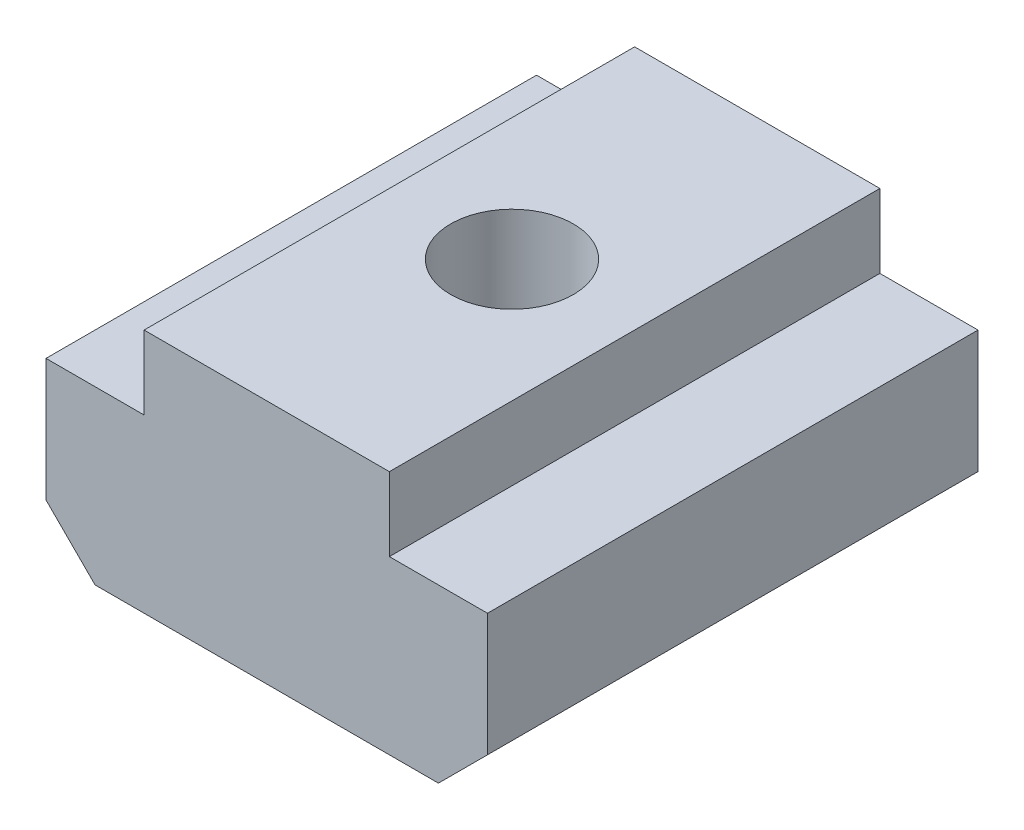
SolidWorks part; units mm, degrees
ref_plane "Front Plane" through (0, 0, 0) normal (0, 0, 1) x (1, 0, 0)
ref_plane "Top Plane" through (0, 0, 0) normal (0, 1, 0) x (1, 0, 0)
ref_plane "Right Plane" through (0, 0, 0) normal (1, 0, 0) x (0, 0, -1)
sketch "Sketch1" plane through (0, 0, 0) normal (0, 0, 1) x (1, 0, 0)
  line L0 (0, 0) -> (0, 46.9655) construction
  line L1 (-3.5, 0) -> (3.5, 0)
  line L2 (3.5, 0) -> (4.5, 1)
  line L3 (4.5, 1) -> (4.5, 3.5)
  line L4 (4.5, 3.5) -> (2.5, 3.5)
  line L5 (2.5, 3.5) -> (2.5, 5)
  line L6 (2.5, 5) -> (-2.5, 5)
  line L7 (-2.5, 5) -> (-2.5, 3.5)
  line L8 (-2.5, 3.5) -> (-4.5, 3.5)
  line L9 (-4.5, 3.5) -> (-4.5, 1)
  line L10 (-4.5, 1) -> (-3.5, 0)
  point P10 (0, 5)
  point P14 (-4.5, 2.25)
  dimension "D1" = 5
  dimension "D2" = 9
  dimension "D3" = 4.5
  dimension "D4" = 1.5
  dimension "D5" = 5
  dimension "D6" = 1
  dimension "D7" = 1
  dimension "D8" = 1
extrude "Boss-Extrude1" add sketch "Sketch1" along normal blind 10
sketch "Sketch2" plane through (0, 5, 0) normal (0, 1, 0) x (1, 0, 0)
  line L0 (-2.5, 0) -> (2.5, -10) construction
  point P4 (0, -5)
hole_wizard "M3x0.5 Tapped Hole1" positions "Sketch3" profile "Sketch4" tap size "M3x0.5" standard "ANSI Metric" end condition through all
sketch "Sketch3" plane through (0, 5, 0) normal (0, 1, 0) x (1, 0, 0)
  point P0 (0, -5)
sketch "Sketch4" plane through (0, 5, 5) normal (1, 0, 0) x (0, 0, 1)
  line L0 (0, 0) -> (0, 5)
  line L1 (0, 5) -> (1.25, 5)
  line L2 (1.25, 5) -> (1.25, 0)
  line L5 (1.25, 0) -> (0, 0)
  line L11 (0, -6.35) -> (0, 107.95) construction
  dimension "Thru Tap Drill Dia." = 2.5
  dimension "Thru Tap Drill Depth" = 5
cosmetic thread "Hole Thread1" parameters "D2"=3
